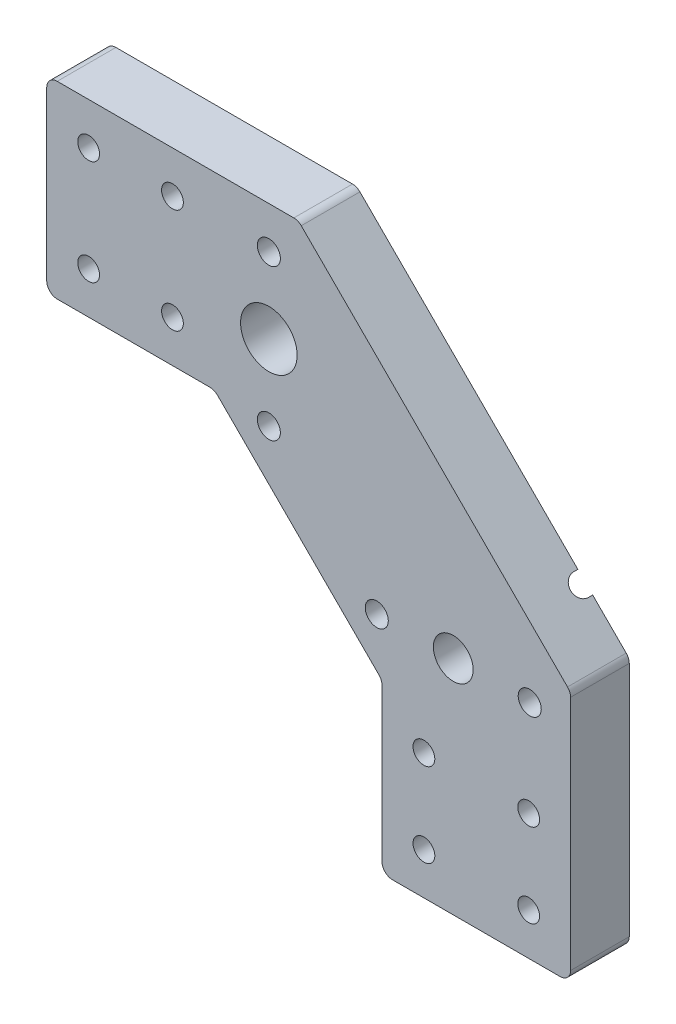
SolidWorks part; units mm, degrees
ref_plane "Спереди" through (0, 0, 0) normal (0, 0, 1) x (1, 0, 0)
ref_plane "Сверху" through (0, 0, 0) normal (0, 1, 0) x (1, 0, 0)
ref_plane "Справа" through (0, 0, 0) normal (1, 0, 0) x (0, 0, -1)
sketch "Эскиз1" plane through (0, 0, 0) normal (0, 0, 1) x (1, 0, 0)
  line L17 (0, 85) -> (0, 0) construction
  line L18 (0, 0) -> (85, 0) construction
  line L19 (-40, -40) -> (85, -40) construction
  line L20 (-40, 85) -> (-40, -40) construction
  line L22 (40, 0) -> (40, -40)
  line L23 (40, 0) -> (0, 40)
  line L24 (0, 40) -> (-40, 40)
  line L31 (40, -40) -> (85, -40)
  line L32 (85, -40) -> (85, 20)
  line L33 (85, 20) -> (20, 85)
  line L34 (20, 85) -> (-40, 85)
  line L35 (-40, 85) -> (-40, 40)
  circle A0 centre (13, 57) radius 6.75
  circle A1 centre (57, 13) radius 4.75
  dimension "D7" = 13.5
  dimension "D8" = 9.5
  dimension "D4" = 44
  dimension "D10" = 44
  dimension "D11" = 40
  dimension "D13" = 45
  dimension "D14" = 45
  dimension "D15" = 13
  dimension "D16" = 60
  dimension "D2" = 40
  dimension "D3" = 40
  dimension "D5" = 40
  dimension "D6" = 20
  dimension "D9" = 13
  dimension "D12" = 13
extrude "Бобышка-Вытянуть2" add sketch "Эскиз1" along normal blind 14
sketch "Эскиз7" plane through (0, 0, 14) normal (0, 0, 1) x (1, 0, 0)
  line L0 (38.75, 13) -> (57, 31.25) construction
  line L1 (57, 31.25) -> (75.25, 13) construction
  line L2 (13, 39) -> (13, 75) construction
  line L3 (75.25, 13) -> (38.75, 13) construction
  line L4 (85, 20) -> (20, 85) construction
  circle A10 centre (13, 39) radius 2.75
  circle A11 centre (13, 57) radius 6.75 construction
  circle A13 centre (13, 75) radius 2.75
  circle A14 centre (38.75, 13) radius 2.75
  circle A15 centre (75.25, 13) radius 2.75
  circle A19 centre (57, 13) radius 4.75 construction
  point P4 (13, 57)
  point P5 (13, 57)
  point P7 (57, 13)
  dimension "D13" = 18
  dimension "D16" = 18
  dimension "D2" = 5.5
  dimension "D3" = 36.5
extrude "Вырез-Вытянуть6" cut sketch "Эскиз7" against normal through all
sketch "Эскиз8" plane through (0, 0, 0) normal (0, 0, -1) x (-1, 0, 0)
  line L1 (-17.7343, 75) -> (-15.3671, 70.9)
  line L2 (-15.3671, 70.9) -> (-10.6329, 70.9)
  line L3 (-10.6329, 70.9) -> (-8.2657, 75)
  line L4 (-8.2657, 75) -> (-10.6329, 79.1)
  line L5 (-10.6329, 79.1) -> (-15.3671, 79.1)
  line L6 (-15.3671, 79.1) -> (-17.7343, 75)
  line L7 (-17.7343, 39) -> (-15.3671, 34.9)
  line L8 (-15.3671, 34.9) -> (-10.6329, 34.9)
  line L9 (-10.6329, 34.9) -> (-8.2657, 39)
  line L10 (-8.2657, 39) -> (-10.6329, 43.1)
  line L11 (-10.6329, 43.1) -> (-15.3671, 43.1)
  line L12 (-15.3671, 43.1) -> (-17.7343, 39)
  line L25 (-34.0157, 13) -> (-36.3829, 17.1)
  line L26 (-36.3829, 17.1) -> (-41.1171, 17.1)
  line L27 (-41.1171, 17.1) -> (-43.4843, 13)
  line L28 (-43.4843, 13) -> (-41.1171, 8.9)
  line L29 (-41.1171, 8.9) -> (-36.3829, 8.9)
  line L30 (-36.3829, 8.9) -> (-34.0157, 13)
  line L31 (-70.5157, 13) -> (-72.8829, 17.1)
  line L32 (-72.8829, 17.1) -> (-77.6171, 17.1)
  line L33 (-77.6171, 17.1) -> (-79.9843, 13)
  line L34 (-79.9843, 13) -> (-77.6171, 8.9)
  line L35 (-77.6171, 8.9) -> (-72.8829, 8.9)
  line L36 (-72.8829, 8.9) -> (-70.5157, 13)
  circle A0 centre (-13, 75) radius 4.1 construction
  circle A1 centre (-13, 39) radius 4.1 construction
  circle A2 centre (-38.75, 13) radius 4.1 construction
  circle A3 centre (-75.25, 13) radius 4.1 construction
  circle A8 centre (-13, 75) radius 2.75 construction
  circle A9 centre (-13, 39) radius 2.75 construction
  dimension "D1" = 8.2
extrude "Вырез-Вытянуть7" cut sketch "Эскиз8" against normal blind 4.2
sketch "Эскиз11" plane through (0, 0, 14) normal (0, 0, 1) x (1, 0, 0)
  line L0 (40, -40) -> (85, -40) construction
  line L1 (40, 0) -> (40, -40) construction
  line L2 (50, -30) -> (75, -30) construction
  line L3 (50, -30) -> (50, -10) construction
  line L4 (20, 20) -> (35375.3391, 35375.3391) construction
  line L7 (85, 20) -> (20, 85) construction
  circle A0 centre (50, -30) radius 2.6
  circle A1 centre (75, -30) radius 2.6
  circle A2 centre (75, -10) radius 2.6
  circle A3 centre (50, -10) radius 2.6
  circle A4 centre (-10, 50) radius 2.6
  circle A5 centre (-30, 50) radius 2.6
  circle A6 centre (-30, 75) radius 2.6
  circle A7 centre (-10, 75) radius 2.6
  point P19 (52.5, 52.5)
  dimension "D1" = 5.2
  dimension "D2" = 10
  dimension "D3" = 10
  dimension "D6" = 90
  dimension "D7" = 25
  dimension "D8" = 20
  dimension "D4" = 2
  dimension "D5" = 2
extrude "Вырез-Вытянуть10" cut sketch "Эскиз11" against normal through all
sketch "Эскиз12" plane through (0, 0, 0) normal (0, 0, -1) x (-1, 0, 0)
  circle A0 centre (-57, 13) radius 8.5
  dimension "D1" = 17
extrude "Вырез-Вытянуть11" cut sketch "Эскиз12" against normal blind 7
sketch "Эскиз13" plane through (52.5, 52.5, 0) normal (0.7071, 0.7071, 0) x (0, 0, -1)
  line L2 (-14, -26.3627) -> (-14, -35.8627) construction
  line L3 (-14, -26.3627) -> (-14, -35.8627) construction
  line L4 (-14, -31.1127) -> (0, -31.1127) construction
  line L5 (0, -45.9619) -> (0, 45.9619) construction
  line L6 (-1, -33.6127) -> (0, -33.6127)
  line L7 (-1, -28.6127) -> (0, -28.6127)
  line L8 (0, -28.6127) -> (0, -33.6127)
  arc A1 (-1, -28.6127) -> (-1, -33.6127) centre (-1, -31.1127) ccw
  dimension "D1" = 5
  dimension "D2" = 1
extrude "Вырез-Вытянуть12" cut sketch "Эскиз13" against normal up to surface (16.6247 mm away)
fillet "Скругление1" radius 2.5 8 edges at (-40, 40, 7) (0, 40, 7) (40, 0, 7) (40, -40, 7) (85, -40, 7) (-40, 85, 7) (20, 85, 7) (85, 20, 7)
